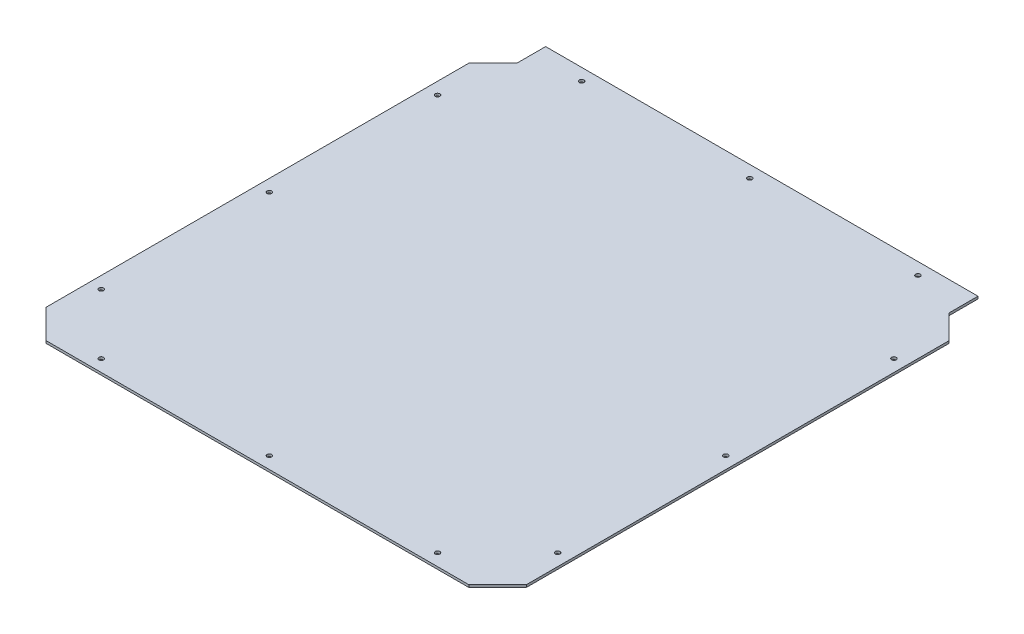
SolidWorks part; units mm, degrees
ref_plane "Front Plane" through (0, 0, 0) normal (0, 0, 1) x (1, 0, 0)
ref_plane "Top Plane" through (0, 0, 0) normal (0, 1, 0) x (1, 0, 0)
ref_plane "Right Plane" through (0, 0, 0) normal (1, 0, 0) x (0, 0, -1)
sketch "Sketch1" plane through (0, 0, 0) normal (0, 1, 0) x (1, 0, 0)
  line L1 (300, -315) -> (-300, -315)
  line L2 (300, -315) -> (300, 315)
  line L3 (300, 315) -> (-300, 315)
  line L4 (-300, -315) -> (-300, 315)
  line L5 (300, -315) -> (-300, 315) construction
  line L6 (300, 315) -> (-300, -315) construction
  point P0 (0, 0)
  dimension "D1" = 630
  dimension "D2" = 600
extrude "Boss-Extrude1" add sketch "Sketch1" along normal mid plane 3
sketch "Sketch2" plane through (0, 1.5, 0) normal (0, 1, 0) x (1, 0, 0)
  line L0 (270, 315) -> (270, 279)
  line L1 (300, 315) -> (-300, 315) construction
  line L2 (270, 279) -> (300, 249)
  line L3 (300, -315) -> (300, 315) construction
  line L4 (300, 249) -> (300, 315)
  line L5 (300, 315) -> (270, 315)
  line L6 (-270, 315) -> (-300, 315)
  line L7 (-300, 315) -> (-300, 249)
  line L8 (-300, 315) -> (-300, -315) construction
  line L9 (-300, 249) -> (-270, 279)
  line L10 (-270, 279) -> (-270, 315)
  line L11 (-300, -315) -> (-300, -279)
  line L12 (-300, -279) -> (-264, -315)
  line L13 (-300, -315) -> (300, -315) construction
  line L14 (-264, -315) -> (-300, -315)
  line L15 (264, -315) -> (300, -315)
  line L16 (300, -315) -> (300, -279)
  line L17 (300, -279) -> (264, -315)
  line L18 (-300, 249) -> (300, 249) construction
  dimension "D1" = 36
  dimension "D2" = 30
  dimension "D3" = 66
extrude "Cut-Extrude1" cut sketch "Sketch2" against normal through all
hole_wizard "M5 Clearance Hole2" positions "Sketch5" profile "Sketch6" hole size "M5" standard "DIN" end condition through all
sketch "Sketch5" plane through (0, 1.5, 0) normal (0, 1, 0) x (1, 0, 0)
  line L0 (0, 300) -> (0, -300) construction
  line L2 (-210, 300) -> (0, 300) construction
  line L3 (0, 300) -> (210, 300) construction
  line L4 (210, 300) -> (210, -300) construction
  line L5 (210, -300) -> (0, -300) construction
  line L6 (0, -300) -> (-210, -300) construction
  line L7 (-210, -300) -> (-210, 300) construction
  line L10 (270, 315) -> (-270, 315) construction
  line L11 (-270, 279) -> (-270, 315) construction
  line L12 (-285, 195) -> (285, 195) construction
  line L13 (285, 195) -> (285, -15) construction
  line L14 (285, -15) -> (285, -225) construction
  line L15 (285, -225) -> (-285, -225) construction
  line L16 (-285, -225) -> (-285, -15) construction
  line L17 (-285, -15) -> (-285, 195) construction
  line L19 (-285, -15) -> (-300, -15) construction
  line L20 (-300, 249) -> (-300, -279) construction
  line L25 (-264, -315) -> (264, -315) construction
  point P0 (-210, 300)
  point P2 (0, 300)
  point P4 (210, 300)
  point P6 (285, 195)
  point P8 (285, -15)
  point P10 (285, -225)
  point P12 (210, -300)
  point P14 (0, -300)
  point P16 (-210, -300)
  point P18 (-285, -225)
  point P20 (-285, -15)
  point P22 (-285, 195)
  point P46 (-270, 297)
  point P68 (265.7257, 195)
  point P69 (0, 195)
  dimension "D1" = 15
  dimension "D2" = 60
  dimension "D3" = 15
  dimension "D4" = 90
sketch "Sketch6" plane through (-210, 1.5, -300) normal (1, 0, 0) x (0, 0, 1)
  line L0 (0, 0) -> (0, 3)
  line L1 (0, 3) -> (2.9, 3)
  line L2 (2.9, 3) -> (2.9, 0)
  line L5 (2.9, 0) -> (0, 0)
  line L11 (0, -6.35) -> (0, 107.95) construction
  dimension "Thru Hole Dia." = 5.8
  dimension "Thru Hole Depth" = 3
